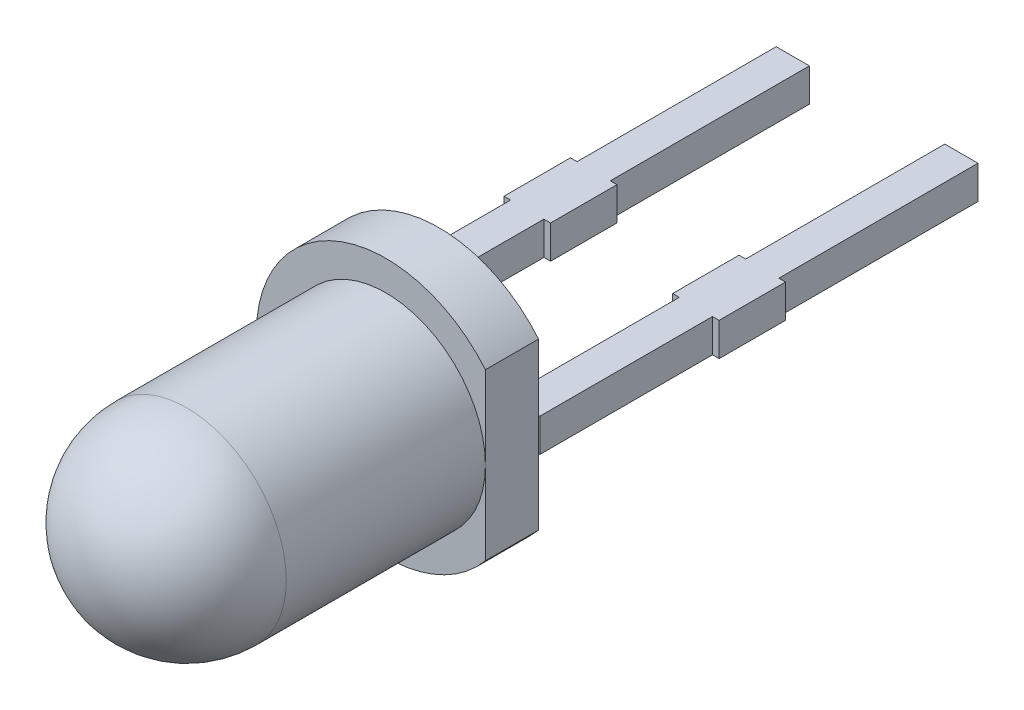
SolidWorks part; units mm, degrees
ref_plane "Front" through (0, 0, 0) normal (0, 0, 1) x (1, 0, 0)
ref_plane "Top" through (0, 0, 0) normal (0, 1, 0) x (1, 0, 0)
ref_plane "Right" through (0, 0, 0) normal (1, 0, 0) x (0, 0, -1)
sketch "Эскиз1" plane through (0, 0, 0) normal (0, -1, 0) x (1, 0, 0)
  line L0 (1.27, 0) -> (-1.27, 0) construction
  line L3 (-1.27, -3) -> (-1.27, 3.6) construction
  line L4 (-1.52, 3.6) -> (-1.52, 1)
  line L5 (-1.52, 1) -> (-1.62, 1)
  line L6 (-1.62, 1) -> (-1.62, 0)
  line L7 (-1.62, 0) -> (-1.52, 0)
  line L8 (-1.52, 0) -> (-1.52, -3)
  line L9 (-1.52, -3) -> (-1.02, -3)
  line L10 (-1.02, 1) -> (-1.02, 0) construction
  line L11 (-1.52, 1) -> (-1.52, 0) construction
  line L12 (-1.02, 0) -> (-1.02, -3)
  line L13 (-0.92, 0) -> (-1.02, 0)
  line L14 (-0.92, 1) -> (-0.92, 0)
  line L15 (-1.02, 1) -> (-0.92, 1)
  line L16 (-1.02, 3.6) -> (-1.02, 1)
  line L17 (1.52, 1) -> (1.52, 0) construction
  line L18 (1.02, 1) -> (1.02, 0) construction
  line L19 (1.02, 3.6) -> (1.02, 1)
  line L20 (1.02, 1) -> (0.92, 1)
  line L21 (0.92, 1) -> (0.92, 0)
  line L22 (0.92, 0) -> (1.02, 0)
  line L23 (1.02, 0) -> (1.02, -3)
  line L24 (1.52, -3) -> (1.02, -3)
  line L25 (1.52, 0) -> (1.52, -3)
  line L26 (1.62, 0) -> (1.52, 0)
  line L27 (1.62, 1) -> (1.62, 0)
  line L28 (1.52, 1) -> (1.62, 1)
  line L29 (1.52, 3.6) -> (1.52, 1)
  line L30 (1.27, -3) -> (1.27, 3.6) construction
  line L59 (-1.52, 3.6) -> (-1.02, 3.6)
  line L60 (1.02, 3.6) -> (1.52, 3.6)
  line L61 (-1.02, 3.6) -> (1.02, 3.6) construction
  point P19 (-1.27, -3)
  point P34 (1.27, -3)
  dimension "D4" = 2.6
  dimension "D1" = 0.5
  dimension "D2" = 2.54
  dimension "D3" = 0.7
  dimension "D5" = 1
  dimension "D6" = 3
extrude "Бобышка-Вытянуть1" add sketch "Эскиз1" along normal mid plane 0.5
sketch "Эскиз2" plane through (0, 0, 0) normal (0, 1, 0) x (1, 0, 0)
  line L0 (0, -3.6) -> (0, -8.9)
  line L1 (1.5, -7.4) -> (1.5, -4.4)
  line L2 (1.95, -3.6) -> (0, -3.6)
  line L3 (1.5, -4.4) -> (1.95, -4.4)
  line L4 (1.95, -4.4) -> (1.95, -3.6)
  line L5 (1.52, -3.6) -> (1.02, -3.6) construction
  line L6 (0, -3.6) -> (0, 0) construction
  arc A0 (1.5, -7.4) -> (0, -8.9) centre (0, -7.4) cw
  dimension "D1" = 3
  dimension "D2" = 3.9
  dimension "D3" = 0.8
  dimension "D4" = 4.5
revolve "Повернуть1" add sketch "Эскиз2" angle 360 about L6
sketch "Эскиз3" plane through (0, 0, 4.4) normal (0, 0, 1) x (1, 0, 0)
  line L0 (1.5, 1.246) -> (1.5, -1.246)
  circle A0 centre (0, 0) radius 1.5 construction
  circle A1 centre (0, 0) radius 1.95 construction
  arc A3 (1.5, 1.246) -> (1.5, -1.246) centre (0, 0) cw
extrude "Вырез-Вытянуть1" cut sketch "Эскиз3" against normal up to surface (0.8 mm away) up to face at (1.27, 0, 3.6)
